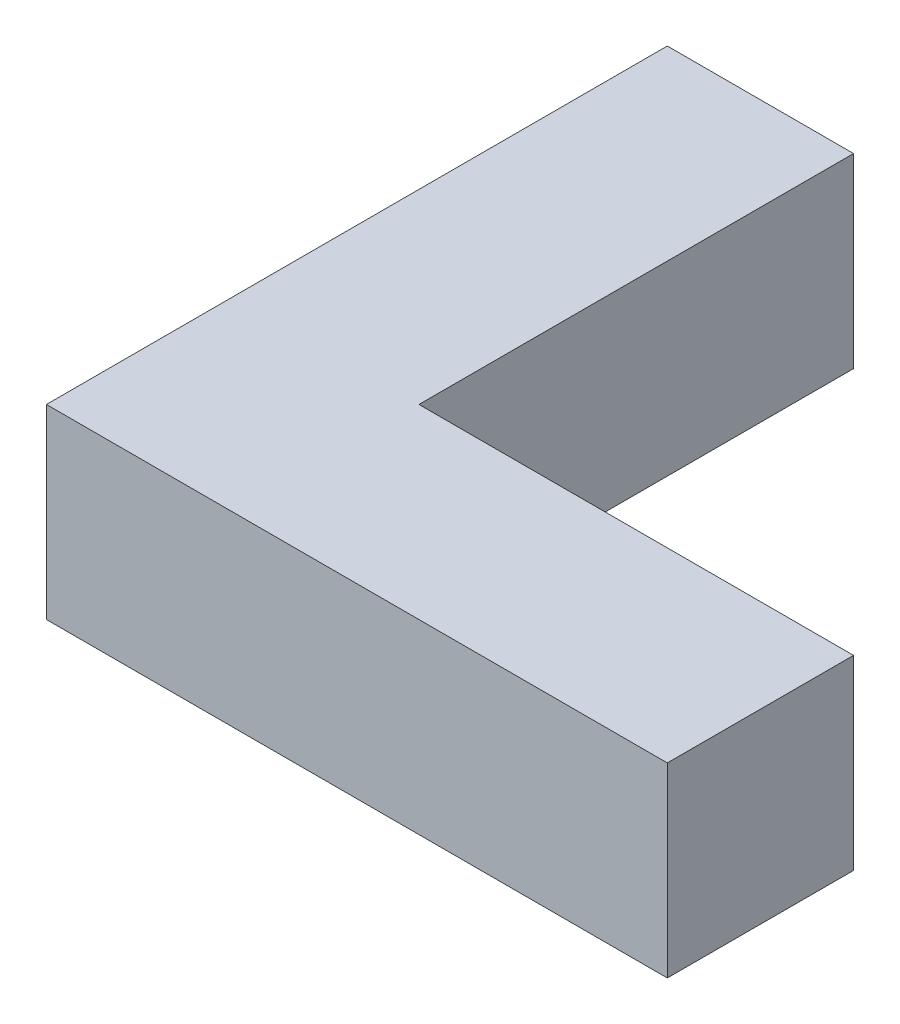
SolidWorks part; units mm, degrees
ref_plane "Front Plane" through (0, 0, 0) normal (0, 0, 1) x (1, 0, 0)
ref_plane "Top Plane" through (0, 0, 0) normal (0, 1, 0) x (1, 0, 0)
ref_plane "Right Plane" through (0, 0, 0) normal (1, 0, 0) x (0, 0, -1)
sketch "Sketch1" plane through (0, 0, 0) normal (0, 1, 0) x (1, 0, 0)
  line L0 (0, 0) -> (0, 10)
  line L1 (0, 10) -> (3, 10)
  line L2 (3, 10) -> (3, 3)
  line L3 (3, 3) -> (10, 3)
  line L4 (10, 3) -> (10, 0)
  line L5 (10, 0) -> (0, 0)
  dimension "D1" = 10
  dimension "D2" = 10
  dimension "D3" = 3
  dimension "D4" = 3
extrude "Boss-Extrude1" add sketch "Sketch1" along normal blind 3
